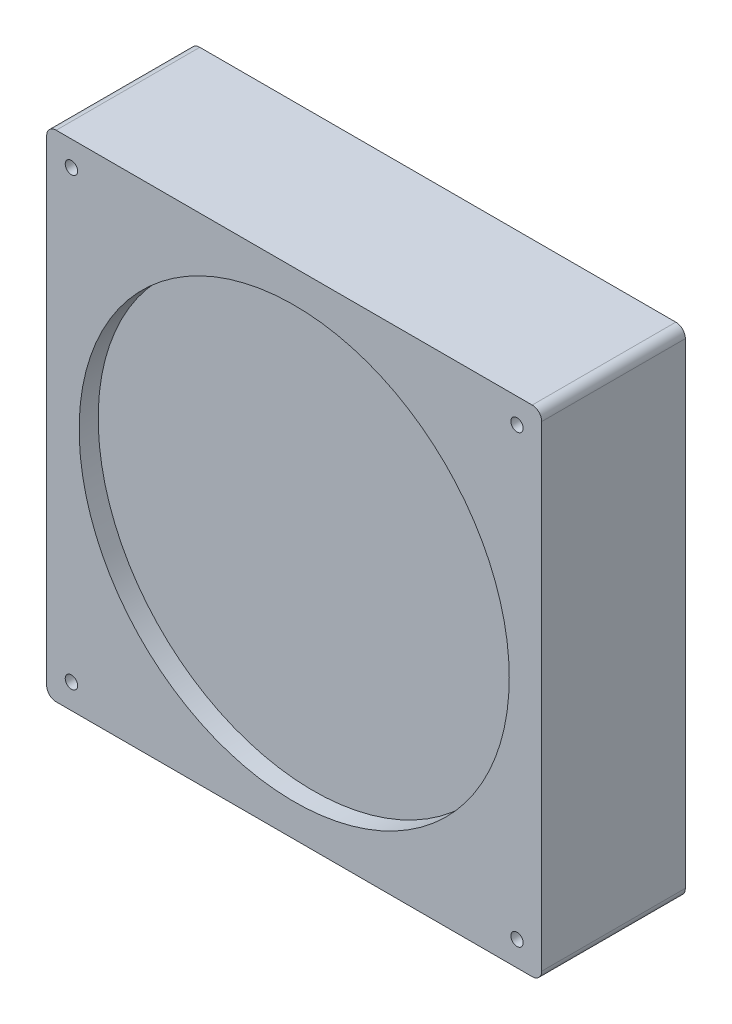
SolidWorks part; units mm, degrees
ref_plane "Front Plane" through (0, 0, 0) normal (0, 0, 1) x (1, 0, 0)
ref_plane "Top Plane" through (0, 0, 0) normal (0, 1, 0) x (1, 0, 0)
ref_plane "Right Plane" through (0, 0, 0) normal (1, 0, 0) x (0, 0, -1)
sketch "Sketch1" plane through (0, 0, 0) normal (0, 0, 1) x (1, 0, 0)
  line L1 (-66, 66) -> (66, 66)
  line L2 (-66, 66) -> (-66, -66)
  line L3 (-66, -66) -> (66, -66)
  line L4 (66, 66) -> (66, -66)
  line L5 (-66, 66) -> (66, -66) construction
  line L6 (-66, -66) -> (66, 66) construction
  point P0 (0, 0)
  dimension "D1" = 132
  dimension "D2" = 132
extrude "Boss-Extrude1" add sketch "Sketch1" along normal blind 38.29
fillet "Fillet1" radius 2.54 4 edges at (66, -66, 19.145) (-66, -66, 19.145) (66, 66, 19.145) (-66, 66, 19.145)
hole_wizard "M4x0.7 Tapped Hole1" positions "Sketch2" profile "Sketch3" tap size "M4x0.7" standard "ANSI Metric" end condition through all
sketch "Sketch2" plane through (0, 0, 38.29) normal (0, 0, 1) x (1, 0, 0)
  line L0 (0, 0) -> (-123.1344, 0) construction
  line L2 (0, 0) -> (0, 66) construction
  line L3 (63.46, 66) -> (-63.46, 66) construction
  point P0 (-59.4, 59.4)
  point P2 (59.4, 59.4)
  point P4 (59.4, -59.4)
  point P6 (-59.4, -59.4)
  dimension "D1" = 118.8
  dimension "D2" = 118.8
sketch "Sketch3" plane through (-59.4, 59.4, 38.29) normal (1, 0, 0) x (0, -1, 0)
  line L0 (0, 0) -> (0, 38.29)
  line L1 (0, 38.29) -> (1.65, 38.29)
  line L2 (1.65, 38.29) -> (1.65, 0)
  line L5 (1.65, 0) -> (0, 0)
  line L11 (0, -6.35) -> (0, 107.95) construction
  dimension "Thru Tap Drill Dia." = 3.3
  dimension "Thru Tap Drill Depth" = 38.29
cosmetic thread "Hole Thread1" parameters "D2"=4
cosmetic thread "Hole Thread2" parameters "D2"=4
cosmetic thread "Hole Thread3" parameters "D2"=4
cosmetic thread "Hole Thread4" parameters "D2"=4
sketch "Sketch4" plane through (0, 0, 38.29) normal (0, 0, 1) x (1, 0, 0)
  circle A0 centre (0, 0) radius 57.3415
extrude "Cut-Extrude1" cut sketch "Sketch4" against normal blind 5.08
